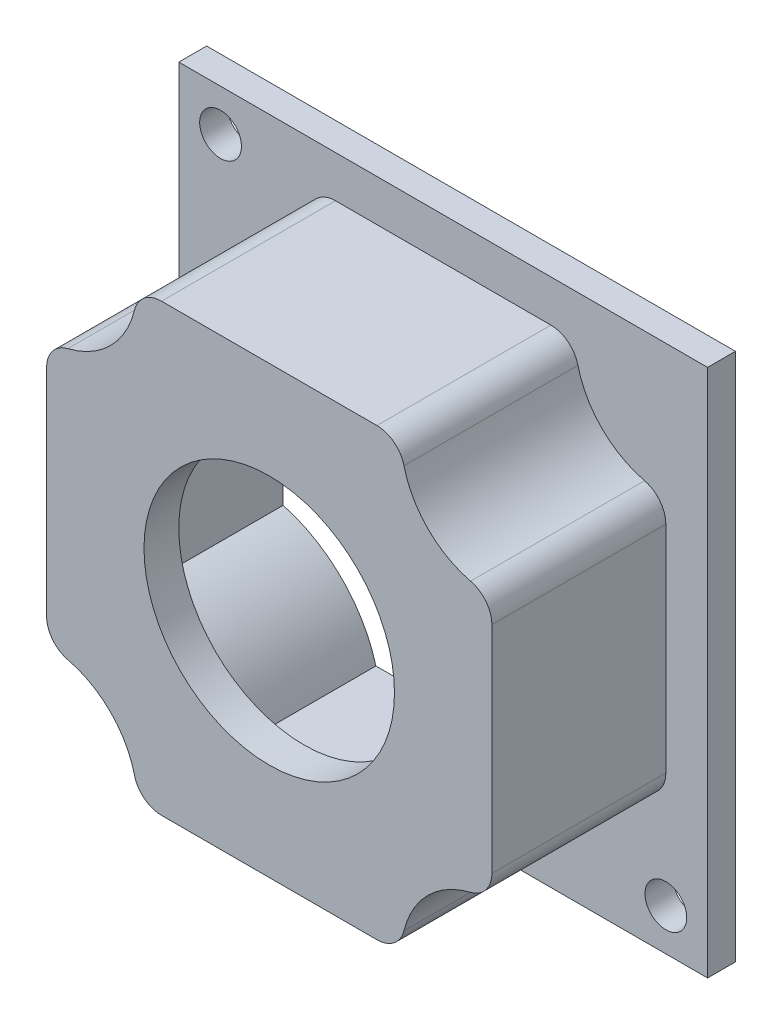
SolidWorks part; units mm, degrees
ref_plane "Front Plane" through (0, 0, 0) normal (1, 0, 0) x (0, 1, 0)
ref_plane "Top Plane" through (0, 0, 0) normal (0, 0, 1) x (0, 1, 0)
ref_plane "Right Plane" through (0, 0, 0) normal (0, 1, 0) x (-1, 0, 0)
sketch "Sketch1" plane through (0, 0, 0) normal (0, 0, 1) x (0, 1, 0)
  line L1 (-19, -19) -> (19, -19)
  line L2 (-19, -19) -> (-19, 19)
  line L3 (-19, 19) -> (19, 19)
  line L4 (19, -19) -> (19, 19)
  line L5 (-19, -19) -> (19, 19) construction
  line L6 (-19, 19) -> (19, -19) construction
  point P0 (0, 0)
  dimension "D1" = 38
extrude "Boss-Extrude1" add sketch "Sketch1" along normal blind 2
sketch "Sketch2" plane through (0, 0, 0) normal (0, 0, -1) x (1, 0, 0)
  line L0 (0, 19) -> (0, -19) construction
  line L1 (-19, 19) -> (19, 19) construction
  line L2 (19, -19) -> (-19, -19) construction
  line L3 (-19, 0) -> (19, 0) construction
  line L4 (-19, -19) -> (-19, 19) construction
  line L5 (19, 19) -> (19, -19) construction
  line L6 (0, 16) -> (-19, 16) construction
  circle A0 centre (-16, 16) radius 1.5
  circle A1 centre (-16, -16) radius 1.5
  circle A2 centre (16, -16) radius 1.5 construction
  circle A3 centre (16, 16) radius 1.5
  dimension "D2" = 3
  dimension "D1" = 16
  dimension "D3" = 16
extrude "Cut-Extrude1" cut sketch "Sketch2" against normal through all
sketch "Sketch3" plane through (0, 0, 2) normal (0, 0, 1) x (1, 0, 0)
  line L0 (-16, 9.5) -> (-16, -9.5)
  line L1 (-9.5, -16) -> (9.5, -16)
  line L2 (16, -9.5) -> (16, 9.5)
  line L3 (-9.5, 16) -> (9.5, 16)
  arc A0 (-16, -9.5) -> (-9.5, -16) centre (-16, -16) cw
  arc A1 (9.5, -16) -> (16, -9.5) centre (16, -16) cw
  arc A2 (-16, 9.5) -> (-9.5, 16) centre (-16, 16) ccw
  arc A3 (9.5, 16) -> (16, 9.5) centre (16, 16) ccw
  circle A4 centre (-16, 16) radius 1.5 construction
  circle A6 centre (16, -16) radius 1.5 construction
  circle A7 centre (-16, -16) radius 1.5 construction
  point P11 (1.8732, 12.209)
  point P13 (0, 0)
  point P16 (0, 0)
  point P19 (0, 0)
  point P22 (0, 0)
  dimension "D1" = 5
  dimension "D2" = 32
extrude "Boss-Extrude2" add sketch "Sketch3" along normal blind 12.5
sketch "Sketch4" plane through (0, 0, 14.5) normal (0, 0, 1) x (1, 0, 0)
  circle A0 centre (0, 0) radius 9
  dimension "D1" = 18
extrude "Cut-Extrude2" cut sketch "Sketch4" against normal through all
sketch "Sketch5" plane through (0, 0, 14.5) normal (0, 0, 1) x (1, 0, 0)
  line L0 (-13.5, -6.8348) -> (-13.5, 6.8348)
  line L1 (-6.8348, 13.5) -> (6.8348, 13.5)
  line L2 (13.5, 6.8348) -> (13.5, -6.8348)
  line L3 (6.8348, -13.5) -> (-6.8348, -13.5)
  line L4 (9.5, 16) -> (-9.5, 16) construction
  line L5 (-16, 9.5) -> (-16, -9.5) construction
  line L6 (-9.5, -16) -> (9.5, -16) construction
  line L7 (16, -9.5) -> (16, 9.5) construction
  arc A0 (-13.5, 6.8348) -> (-6.8348, 13.5) centre (-16, 16) ccw
  arc A1 (6.8348, 13.5) -> (13.5, 6.8348) centre (16, 16) ccw
  arc A2 (13.5, -6.8348) -> (6.8348, -13.5) centre (16, -16) ccw
  arc A3 (-6.8348, -13.5) -> (-13.5, -6.8348) centre (-16, -16) ccw
  circle A4 centre (-16, -16) radius 1.5 construction
  circle A5 centre (-16, 16) radius 1.5 construction
  circle A7 centre (16, -16) radius 1.5 construction
  arc A8 (-16, 9.5) -> (-9.5, 16) centre (-16, 16) ccw construction
  point P11 (-7.6933, -15.7546)
  point P13 (0, 0)
  point P16 (0, 0)
  point P19 (0, 0)
  point P24 (-9.5, -16)
  dimension "D5" = 3
  dimension "D1" = 2.5
  dimension "D2" = 2.5
  dimension "D3" = 2.5
  dimension "D4" = 2.5
extrude "Cut-Extrude3" cut sketch "Sketch5" against normal through all from offset 2.5 offset against normal yes
fillet "Fillet1" radius 2 8 edges at (-16, -9.5, 8.25) (-9.5, -16, 8.25) (9.5, -16, 8.25) (16, -9.5, 8.25) (16, 9.5, 8.25) (9.5, 16, 8.25) (-9.5, 16, 8.25) (-16, 9.5, 8.25)
